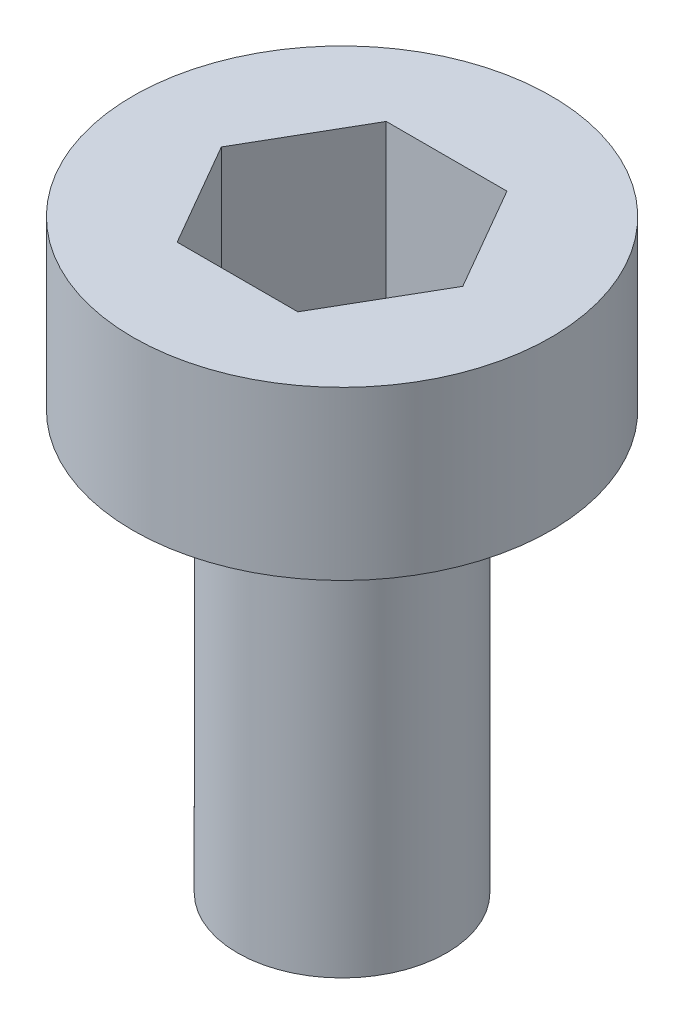
SolidWorks part; units mm, degrees
ref_plane "Front" through (0, 0, 0) normal (0, 0, 1) x (1, 0, 0)
ref_plane "Top" through (0, 0, 0) normal (0, 1, 0) x (1, 0, 0)
ref_plane "Right" through (0, 0, 0) normal (1, 0, 0) x (0, 0, -1)
sketch "Sketch1" plane through (0, 0, 0) normal (0, 1, 0) x (1, 0, 0)
  circle A0 centre (0, 0) radius 2.5
  dimension "D1" = 5
extrude "Extrude1" add sketch "Sketch1" against normal blind 10
sketch "Sketch2" plane through (0, 0, 0) normal (0, 1, 0) x (1, 0, 0)
  line L0 (0, 0) -> (2.8868, 0) construction
  line L1 (2.8868, 0) -> (1.4434, 2.5)
  line L2 (1.4434, 2.5) -> (0, 0) construction
  line L3 (1.4434, -2.5) -> (2.8868, 0)
  line L4 (-1.4434, -2.5) -> (1.4434, -2.5)
  line L5 (-2.8868, 0) -> (-1.4434, -2.5)
  line L6 (-1.4434, 2.5) -> (-2.8868, 0)
  line L7 (1.4434, 2.5) -> (-1.4434, 2.5)
  circle A0 centre (0, 0) radius 5
  dimension "D3" = 10
  dimension "D1" = 60
  dimension "D2" = 2.5
extrude "Extrude2" add sketch "Sketch2" along normal blind 4
